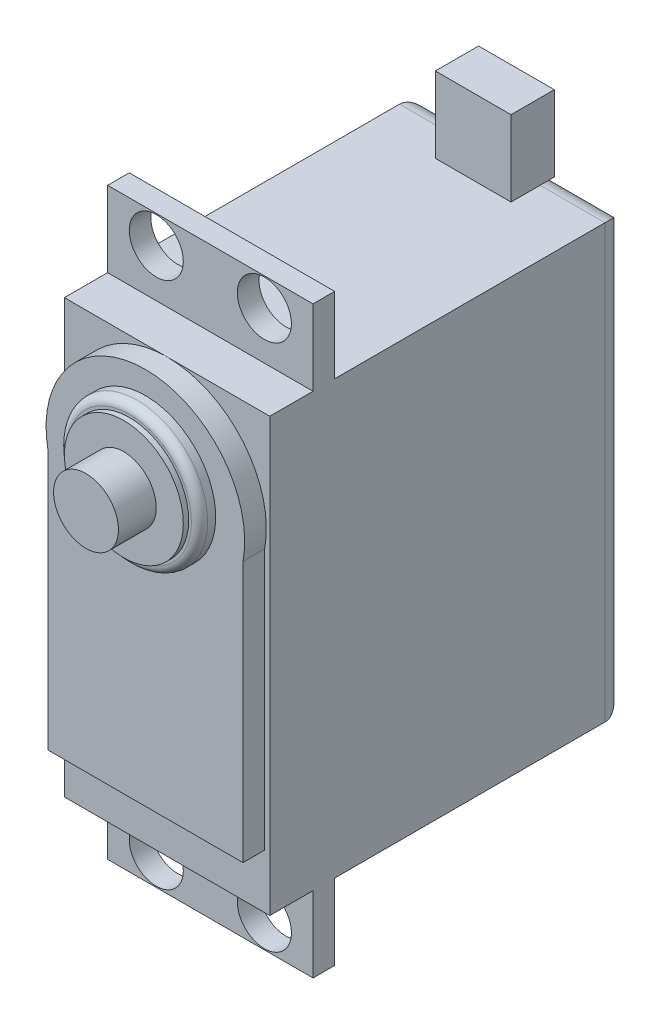
SolidWorks part; units mm, degrees
ref_plane "Plan de face" through (0, 0, 0) normal (0, 0, 1) x (1, 0, 0)
ref_plane "Plan de dessus" through (0, 0, 0) normal (0, 1, 0) x (1, 0, 0)
ref_plane "Plan de droite" through (0, 0, 0) normal (1, 0, 0) x (0, 0, -1)
sketch "Esquisse1" plane through (0, 0, 0) normal (1, 0, 0) x (0, 0, -1)
  line L0 (0, 0) -> (4, 0)
  line L1 (4, 0) -> (4, -7)
  line L2 (4, -7) -> (6, -7)
  line L3 (6, -7) -> (6, 0)
  line L4 (6, 0) -> (33, 0)
  line L5 (33, 0) -> (33, 40)
  line L6 (0, 0) -> (0, 40)
  line L7 (0, 20) -> (33, 20) construction
  line L8 (6, 40) -> (33, 40)
  line L9 (6, 47) -> (6, 40)
  line L10 (4, 47) -> (6, 47)
  line L11 (4, 40) -> (4, 47)
  line L12 (0, 40) -> (4, 40)
  dimension "D1" = 33
  dimension "D2" = 4
  dimension "D3" = 2
  dimension "D4" = 20
  dimension "D5" = 7
extrude "Boss.-Extru.1" add sketch "Esquisse1" along normal mid plane 19
ref_plane "Plan1" through (0, 0, -4) normal (0, 0, 1) x (1, 0, 0)
sketch "Esquisse3" plane through (0, 0, -4) normal (0, 0, 1) x (1, 0, 0)
  line L0 (-9.5, 20) -> (9.5, 20) construction
  line L1 (-9.5, 40) -> (-9.5, 0) construction
  line L2 (9.5, 40) -> (9.5, 0) construction
  line L3 (0, 47) -> (0, 20) construction
  line L4 (9.5, 47) -> (-9.5, 47) construction
  circle A0 centre (5, 44.4) radius 2.5
  circle A1 centre (-5, 44.4) radius 2.5
  circle A2 centre (5, -4.4) radius 2.5
  circle A3 centre (-5, -4.4) radius 2.5
  dimension "D1" = 5
  dimension "D2" = 2.6
  dimension "D3" = 4.5
extrude "Enlèv. mat.-Extru.40" cut sketch "Esquisse3" against normal blind 10
sketch "Esquisse4" plane through (0, 0, 0) normal (0, 0, 1) x (1, 0, 0)
  line L0 (-9.0349, 5) -> (9.0189, 5)
  line L1 (9.0189, 5) -> (9.0189, 29.1109)
  line L2 (-9.0349, 5) -> (-9.0349, 29.1109)
  line L3 (9.5, 0) -> (-9.5, 0) construction
  arc A0 (-9.0349, 29.1109) -> (9.0189, 29.1109) centre (-0.008, 30.8138) cw
  dimension "D1" = 5
extrude "Boss.-Extru.2" add sketch "Esquisse4" along normal blind 2
fillet "Congé1" radius 2 4 edges at (0, 0, -33) (9.5, 20, -33) (0, 40, -33) (-9.5, 20, -33)
sketch "Esquisse5" plane through (0, 0, 2) normal (0, 0, 1) x (1, 0, 0)
  circle A0 centre (0, 31.4091) radius 6.5
  dimension "D1" = 13
extrude "Boss.-Extru.3" add sketch "Esquisse5" along normal blind 1.5
fillet "Congé2" radius 0.75 1 edges at (6.5, 31.4091, 3.5)
sketch "Esquisse6" plane through (0, 0, 3.5) normal (0, 0, 1) x (1, 0, 0)
  circle A0 centre (0, 31.4091) radius 5.5
  dimension "D1" = 11
extrude "Boss.-Extru.4" add sketch "Esquisse6" along normal blind 0.5
sketch "Esquisse7" plane through (0, 0, 4) normal (0, 0, 1) x (1, 0, 0)
  circle A0 centre (0, 31.4091) radius 3
  dimension "D1" = 6
extrude "Boss.-Extru.5" add sketch "Esquisse7" along normal blind 3.5
sketch "Esquisse8" plane through (0, 40, 0) normal (0, 1, 0) x (1, 0, 0)
  line L0 (-3.5, 32.3142) -> (-3.5, 28.3142)
  line L1 (-3.5, 28.3142) -> (3.5, 28.3142)
  line L2 (3.5, 28.3142) -> (3.5, 32.3142)
  line L3 (3.5, 32.3142) -> (-3.5, 32.3142)
  line L4 (0, 31) -> (0, 32.3142) construction
  line L6 (9.5, 31) -> (-9.5, 31) construction
  arc A0 (9.5, 31) -> (7.5, 33) centre (7.5, 31) ccw construction
  point P8 (8.9142, 32.4142)
  dimension "D1" = 0.1
  dimension "D2" = 7
  dimension "D3" = 4
extrude "Boss.-Extru.6" add sketch "Esquisse8" along normal blind 7
